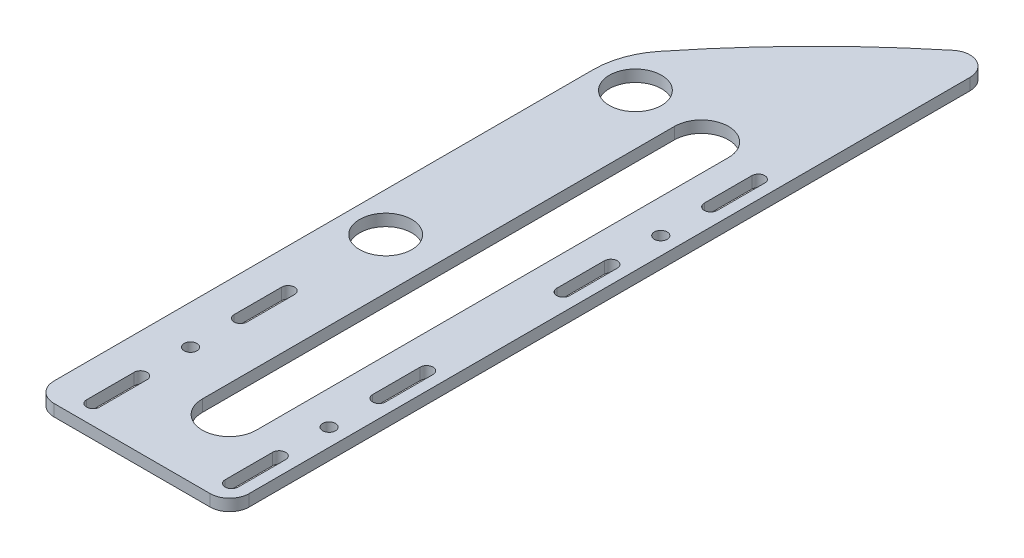
SolidWorks part; units mm, degrees
material "Thornel Mat VMA"
ref_plane "前视基准面" through (0, 0, 0) normal (0, 0, 1) x (1, 0, 0)
ref_plane "上视基准面" through (0, 0, 0) normal (0, 1, 0) x (1, 0, 0)
ref_plane "右视基准面" through (0, 0, 0) normal (1, 0, 0) x (0, 0, -1)
sketch "草图1" plane through (0, 0, 0) normal (0, 1, 0) x (1, 0, 0)
  line L0 (10, 0) -> (10, 96.6984) construction
  line L1 (0, 0) -> (50, 0)
  line L2 (0, 0) -> (0, 150)
  line L4 (50, 0) -> (50, 200)
  line L5 (10, 5) -> (10, 17.2) construction
  line L6 (8.35, 5) -> (8.35, 17.2)
  line L7 (11.65, 5) -> (11.65, 17.2)
  line L9 (10, 42.8) -> (10, 55) construction
  line L10 (8.35, 42.8) -> (8.35, 55)
  line L11 (11.65, 42.8) -> (11.65, 55)
  line L12 (45.5, 0) -> (45.5, 208.9032) construction
  line L13 (45.5, 5) -> (45.5, 17.2) construction
  line L14 (43.85, 5) -> (43.85, 17.2)
  line L15 (47.15, 5) -> (47.15, 17.2)
  line L16 (45.5, 42.8) -> (45.5, 55) construction
  line L17 (43.85, 42.8) -> (43.85, 55)
  line L18 (47.15, 42.8) -> (47.15, 55)
  line L19 (45.5, 90) -> (45.5, 102.2) construction
  line L20 (43.85, 90) -> (43.85, 102.2)
  line L21 (47.15, 90) -> (47.15, 102.2)
  line L22 (45.5, 127.8) -> (45.5, 140) construction
  line L25 (43.85, 127.8) -> (43.85, 140)
  line L26 (47.15, 127.8) -> (47.15, 140)
  circle A0 centre (10, 80) radius 6.7
  circle A1 centre (10, 144) radius 6.7
  arc A5 (0, 150) -> (50, 200) centre (200, 0) cw
  arc A6 (8.35, 5) -> (11.65, 5) centre (10, 5) ccw
  arc A7 (11.65, 17.2) -> (8.35, 17.2) centre (10, 17.2) ccw
  arc A8 (8.35, 42.8) -> (11.65, 42.8) centre (10, 42.8) ccw
  arc A9 (11.65, 55) -> (8.35, 55) centre (10, 55) ccw
  circle A10 centre (10, 30) radius 1.65
  arc A11 (43.85, 5) -> (47.15, 5) centre (45.5, 5) ccw
  arc A12 (47.15, 17.2) -> (43.85, 17.2) centre (45.5, 17.2) ccw
  circle A13 centre (45.5, 30) radius 1.65
  arc A14 (43.85, 42.8) -> (47.15, 42.8) centre (45.5, 42.8) ccw
  arc A15 (47.15, 55) -> (43.85, 55) centre (45.5, 55) ccw
  arc A16 (43.85, 90) -> (47.15, 90) centre (45.5, 90) ccw
  arc A17 (47.15, 102.2) -> (43.85, 102.2) centre (45.5, 102.2) ccw
  circle A18 centre (45.5, 115) radius 1.65
  arc A21 (43.85, 127.8) -> (47.15, 127.8) centre (45.5, 127.8) ccw
  arc A22 (47.15, 140) -> (43.85, 140) centre (45.5, 140) ccw
  point P13 (10, 11.1)
  point P21 (10, 48.9)
  point P32 (45.5, 11.1)
  point P41 (45.5, 48.9)
  point P46 (45.5, 96.1)
  point P57 (45.5, 133.9)
  dimension "D4" = 10
  dimension "D5" = 80
  dimension "D6" = 10
  dimension "D7" = 13.4
  dimension "D8" = 6
  dimension "D10" = 3.3
  dimension "D11" = 3.3
  dimension "D12" = 12.2
  dimension "D3" = 250
  dimension "D15" = 3.3
  dimension "D16" = 25
  dimension "D25" = 3.3
  dimension "D28" = 3.3
  dimension "D1" = 150
  dimension "D2" = 50
  dimension "D9" = 12.2
  dimension "D13" = 50
  dimension "D14" = 5
  dimension "D17" = 4.5
  dimension "D18" = 12.2
  dimension "D19" = 3.3
  dimension "D20" = 5
  dimension "D21" = 12.2
  dimension "D22" = 3.3
  dimension "D23" = 50
  dimension "D24" = 12.8
  dimension "D26" = 3.3
  dimension "D27" = 12.2
  dimension "D29" = 12.8
  dimension "D30" = 50
  dimension "D31" = 12.2
  dimension "D32" = 3.3
  dimension "D33" = 35
extrude "凸台-拉伸1" add sketch "草图1" along normal blind 3
fillet "圆角1" radius 5 3 edges at (0, 1.5, 0) (50, 1.5, 0) (50, 1.5, -200)
fillet "圆角2" radius 20 1 edges at (0, 1.5, -150)
sketch "草图2" plane through (0, 3, 0) normal (0, 1, 0) x (1, 0, 0)
  line L0 (29.925, 141) -> (29.925, 20) construction
  line L1 (36.85, 141) -> (36.85, 20)
  line L2 (23, 141) -> (23, 20)
  line L3 (43.85, 102.2) -> (43.85, 90) construction
  line L4 (5, 0) -> (45, 0) construction
  arc A0 (36.85, 141) -> (23, 141) centre (29.925, 141) ccw
  arc A1 (23, 20) -> (36.85, 20) centre (29.925, 20) ccw
  circle A2 centre (10, 80) radius 6.7 construction
  circle A3 centre (10, 144) radius 6.7 construction
  point P2 (29.925, 80.5)
  dimension "D4" = 3
  dimension "D1" = 13
  dimension "D2" = 7
  dimension "D3" = 20
extrude "切除-拉伸1" cut sketch "草图2" against normal through all
